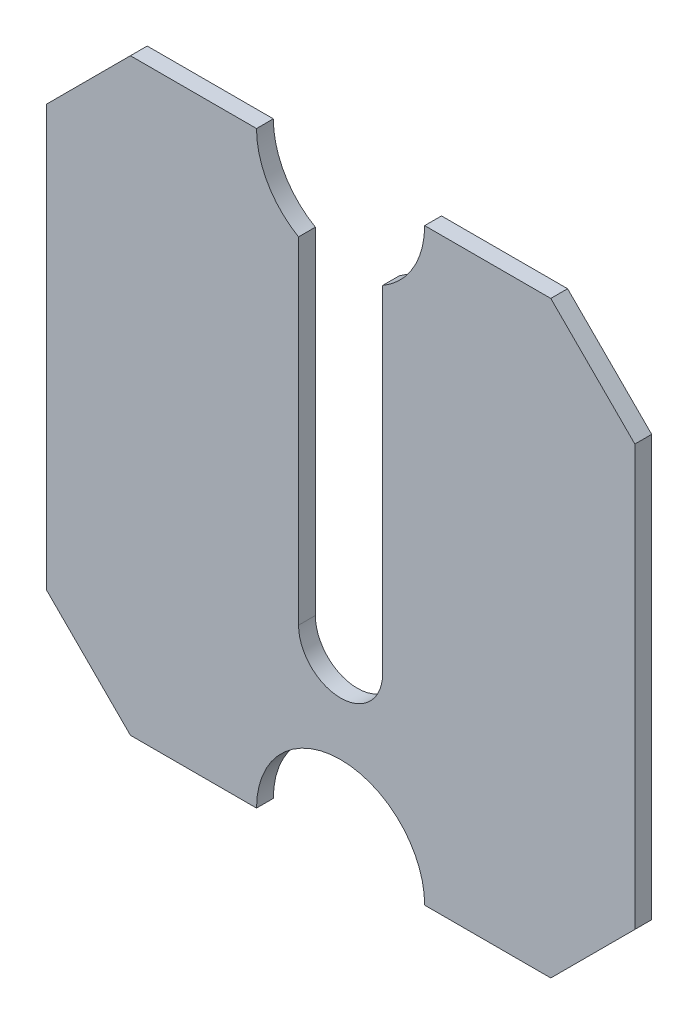
SolidWorks part; units mm, degrees
ref_plane "Front Plane" through (0, 0, 0) normal (0, 0, 1) x (1, 0, 0)
ref_plane "Top Plane" through (0, 0, 0) normal (0, 1, 0) x (1, 0, 0)
ref_plane "Right Plane" through (0, 0, 0) normal (1, 0, 0) x (0, 0, -1)
sketch "Sketch1" plane through (0, 0, 0) normal (0, 0, 1) x (1, 0, 0)
  line L0 (125, 175) -> (50, 175)
  line L1 (-125, -175) -> (-50, -175)
  line L2 (-175, -125) -> (-175, 125)
  line L3 (0, 0) -> (0, -70.9541) construction
  line L4 (175, -125) -> (175, 125)
  line L5 (-175, 0) -> (175, 0) construction
  line L6 (0, -93.3013) -> (0, -125) construction
  line L7 (-125, 175) -> (-125, -175) construction
  line L8 (-25, 131.6987) -> (-25, -68.3013)
  line L9 (-175, 125) -> (-25, 125) construction
  line L10 (125, 175) -> (125, -175) construction
  line L11 (-175, -125) -> (175, -125) construction
  line L12 (-125, 175) -> (-175, 125)
  line L13 (125, 175) -> (175, 125)
  line L14 (125, -175) -> (175, -125)
  line L15 (-125, -175) -> (-175, -125)
  line L16 (50, -175) -> (125, -175)
  line L17 (-50, 175) -> (-125, 175)
  line L18 (25, 131.6987) -> (25, -68.3013)
  line L19 (25, 125) -> (175, 125) construction
  arc A0 (-50, 175) -> (-25, 131.6987) centre (0, 175) ccw
  arc A1 (50, -175) -> (-50, -175) centre (0, -175) ccw
  arc A2 (-25, -68.3013) -> (25, -68.3013) centre (0, -68.3013) ccw
  arc A3 (25, 131.6987) -> (50, 175) centre (0, 175) ccw
  point P21 (0, 0)
  point P28 (0, 0)
  point P29 (0, 0)
  point P30 (0, 0)
  point P31 (0, 0)
  point P33 (0, 0)
  dimension "D1" = 350
  dimension "D5" = 50
  dimension "D6" = 25
  dimension "D8" = 50
  dimension "D2" = 350
  dimension "D3" = 50
  dimension "D4" = 50
  dimension "D7" = 200
  dimension "D9" = 0
  dimension "D10" = 75
  dimension "D11" = 75
  dimension "D12" = 100
  dimension "D13" = 50
  dimension "D14" = 0
extrude "Boss-Extrude1" add sketch "Sketch1" along normal blind 10
ref_plane "Plane1" through (0, -175, 0) normal (0, -1, 0) x (-1, 0, 0)
